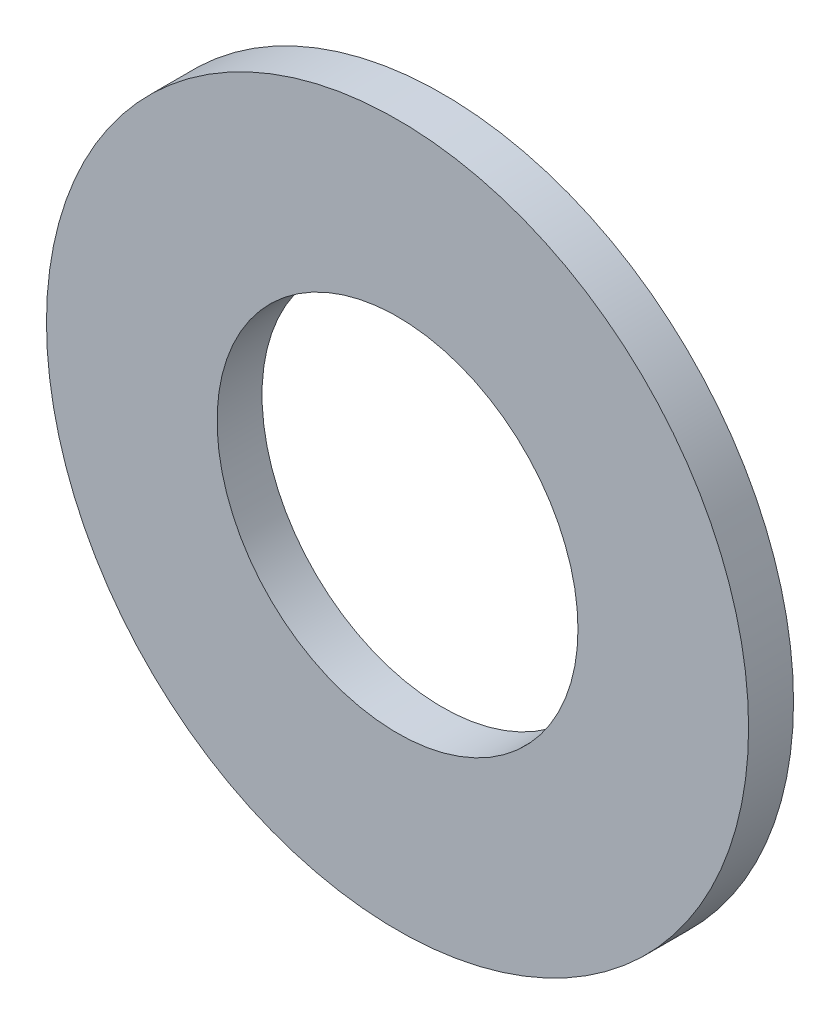
SolidWorks part; units mm, degrees
material "Alloy Steel"
ref_plane "X-Y Datum" through (0, 0, 0) normal (0, 0, 1) x (1, 0, 0)
ref_plane "X-Z Datum" through (0, 0, 0) normal (0, 1, 0) x (1, 0, 0)
ref_plane "Y-Z Datum" through (0, 0, 0) normal (1, 0, 0) x (0, 0, -1)
sketch "Sketch1" plane through (0, 0, 0) normal (0, 0, 1) x (1, 0, 0)
  circle A0 centre (0, 0) radius 6.35
  dimension "D1" = 12.7
extrude "Boss-Extrude1" add sketch "Sketch1" along normal blind 0.8128
hole_wizard "1/4 Clearance Hole1" positions "Sketch2" profile "Sketch3" hole size "1/4" standard "ANSI Inch" end condition through all
sketch "Sketch2" plane through (0, 0, 0.8128) normal (0, 0, 1) x (1, 0, 0)
  point P0 (0, 0)
sketch "Sketch3" plane through (0, 0, 0.8128) normal (1, 0, 0) x (0, -1, 0)
  line L0 (0, 0) -> (0, 0.8128)
  line L1 (0, 0.8128) -> (3.2639, 0.8128)
  line L2 (3.2639, 0.8128) -> (3.2639, 0)
  line L5 (3.2639, 0) -> (0, 0)
  line L11 (0, -6.35) -> (0, 107.95) construction
  dimension "Thru Hole Dia." = 6.5278
  dimension "Thru Hole Depth" = 0.8128
